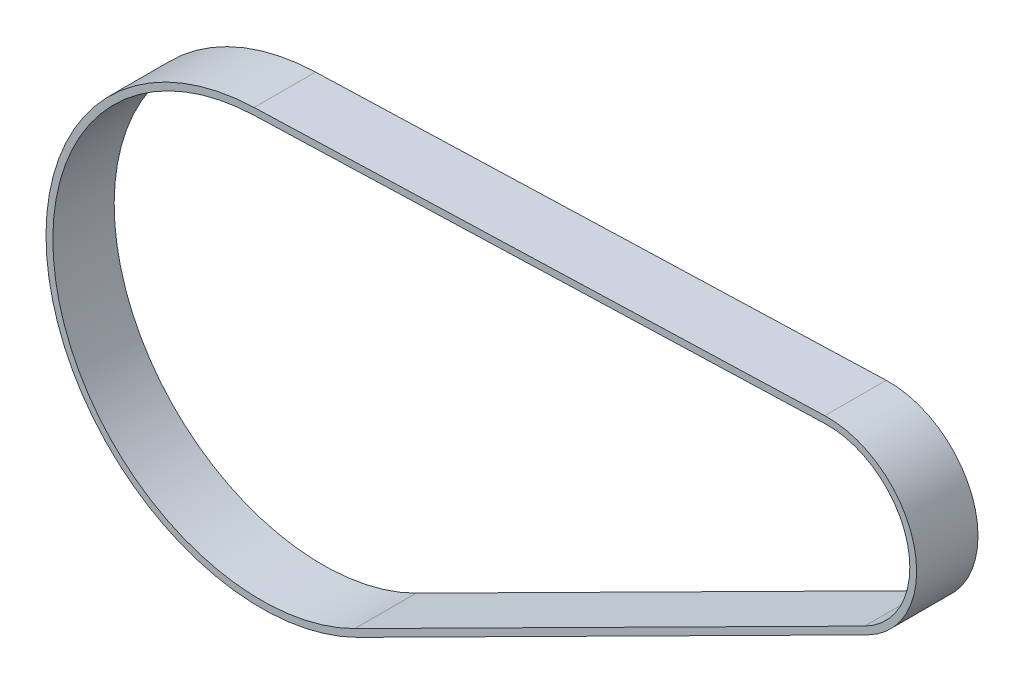
SolidWorks part; units mm, degrees
ref_plane "Front Plane" through (0, 0, 0) normal (0, 0, 1) x (1, 0, 0)
ref_plane "Top Plane" through (0, 0, 0) normal (0, 1, 0) x (1, 0, 0)
ref_plane "Right Plane" through (0, 0, 0) normal (1, 0, 0) x (0, 0, -1)
sketch "Sketch2" plane through (0, 0, 0) normal (0, 0, 1) x (1, 0, 0)
  line L0 (0, 0) -> (1, 0) construction
  line L1 (0, 0) -> (0, 1) construction
  line L2 (-0.9855, 30.5341) -> (82.7267, 33.236)
  line L3 (88.5409, 10.4328) -> (13.7551, -27.2782)
  arc A0 (13.7551, -27.2782) -> (-0.9855, 30.5341) centre (0, 0) cw
  arc A1 (82.7267, 33.236) -> (88.5409, 10.4328) centre (83.1154, 21.1922) cw
extrude "Extrude-Thin1" add sketch "Sketch2" along normal blind 4.5 and the other way blind 4.5 thin thin type one direction wall 1
